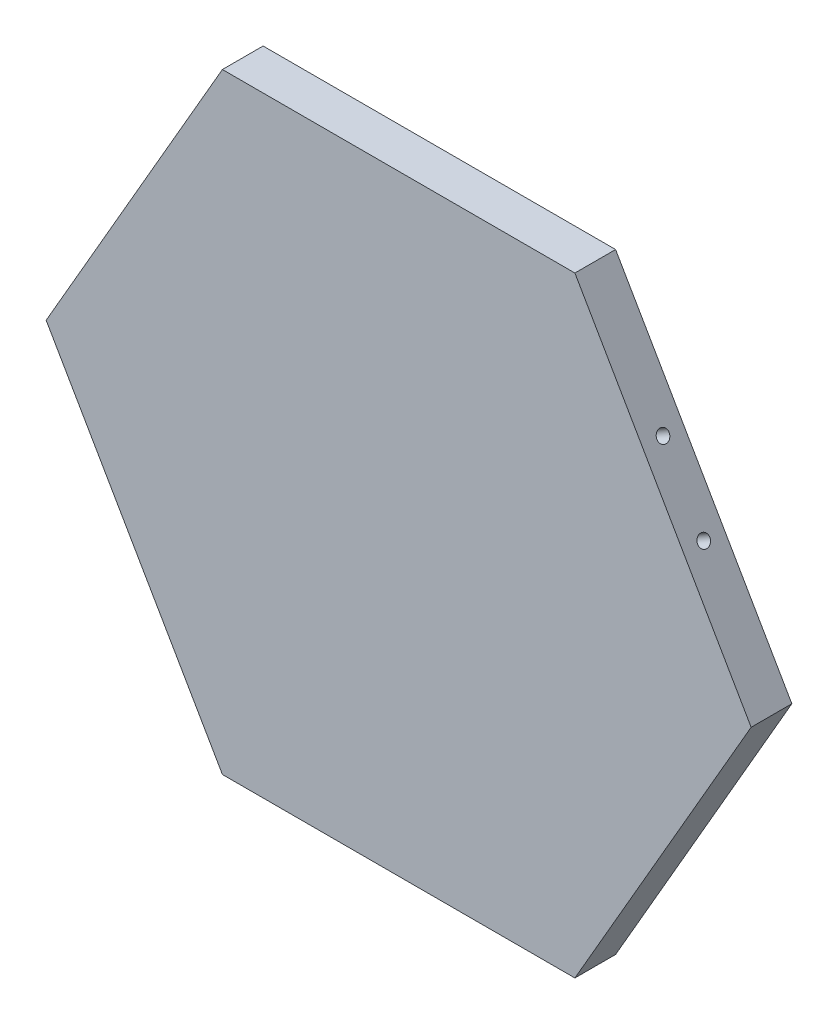
SolidWorks part; units mm, degrees
ref_plane "Top Plane" through (0, 0, 0) normal (0, 0, 1) x (1, 0, 0)
ref_plane "Front Plane" through (0, 0, 0) normal (0, 1, 0) x (1, 0, 0)
ref_plane "Right Plane" through (0, 0, 0) normal (1, 0, 0) x (0, 0, -1)
sketch "Sketch1" plane through (0, 0, 0) normal (0, 0, 1) x (1, 0, 0)
  line L0 (0, 0) -> (28.1683, 0) construction
  line L1 (86.6025, 0) -> (43.3013, 75)
  line L2 (43.3013, 75) -> (-43.3013, 75)
  line L3 (-43.3013, 75) -> (-86.6025, 0)
  line L4 (-86.6025, 0) -> (-43.3013, -75)
  line L5 (-43.3013, -75) -> (43.3013, -75)
  line L6 (43.3013, -75) -> (86.6025, 0)
  circle A0 centre (0, 0) radius 75 construction
  point P10 (86.6025, 0)
  dimension "D1" = 150
extrude "Boss-Extrude1" add sketch "Sketch1" along normal blind 10
sketch "Sketch2" plane through (0, -75, 0) normal (0, -1, 0) x (1, 0, 0)
  line L0 (-43.3013, 0) -> (43.3013, 0) construction
  circle A0 centre (-10, 5) radius 1.5
  circle A1 centre (10, 5) radius 1.5
  dimension "D1" = 10
  dimension "D2" = 5
  dimension "D3" = 3
  dimension "D5" = 10
extrude "Cut-Extrude1" cut sketch "Sketch2" against normal blind 5
pattern_circular "CirPattern1" count 3 over 360 about axis through (0, 0, 0) along (0, 0, 1) of "Cut-Extrude1"
